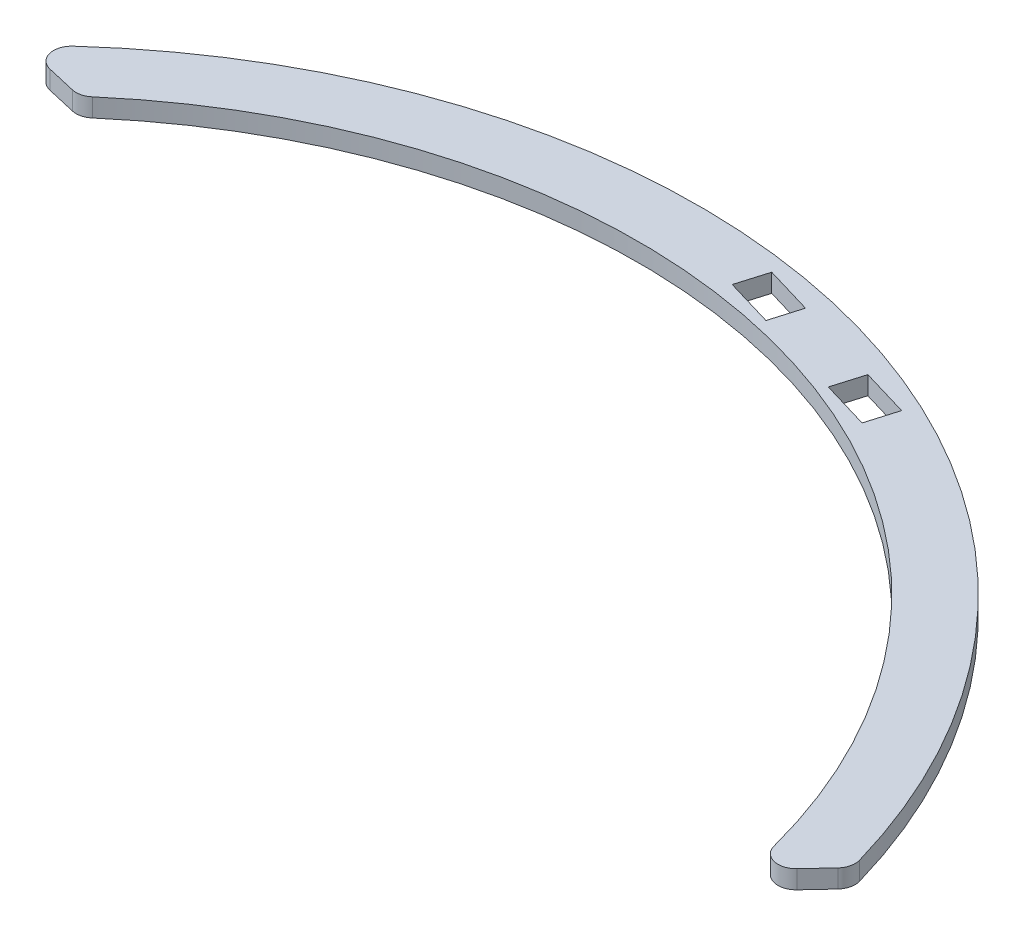
SolidWorks part; units mm, degrees
ref_plane "Спереди" through (0, 0, 0) normal (0, 0, 1) x (1, 0, 0)
ref_plane "Сверху" through (0, 0, 0) normal (0, 1, 0) x (1, 0, 0)
ref_plane "Справа" through (0, 0, 0) normal (1, 0, 0) x (0, 0, -1)
other "Configuration Table"
sketch "Эскиз2" plane through (0, 0, 0) normal (0, 1, 0) x (1, 0, 0)
  line L0 (97.9755, 20.0202) -> (106.1654, 28.7909)
  line L1 (-66.3257, 74.8391) -> (-78.0163, 77.5464)
  arc A0 (97.9755, 20.0202) -> (-66.3257, 74.8391) centre (0, 0) ccw
  arc A1 (106.1654, 28.7909) -> (-78.0163, 77.5464) centre (0, 0) ccw
  dimension "D1" = 110
  dimension "D3" = 100
  dimension "D2" = 12
  dimension "D4" = 120
extrude "Бобышка-Вытянуть1" add sketch "Эскиз2" along normal blind 3
sketch "Эскиз3" plane through (0, 3, 0) normal (0, 1, 0) x (1, 0, 0)
  line L0 (-78.0163, 77.5464) -> (-66.3257, 74.8391) construction
  line L5 (36.109, 94.9201) -> (43.9692, 92.584)
  line L6 (36.109, 94.9201) -> (37.5905, 99.9046)
  line L7 (37.5905, 99.9046) -> (45.4506, 97.5685)
  line L8 (43.9692, 92.584) -> (45.4506, 97.5685)
  line L9 (97.9755, 20.0202) -> (106.1654, 28.7909) construction
  line L10 (-72.171, 76.1928) -> (102.0704, 24.4056)
  line L11 (13.7363, 101.5696) -> (21.5964, 99.2335)
  line L12 (13.7363, 101.5696) -> (15.2177, 106.5541)
  line L13 (15.2177, 106.5541) -> (23.0779, 104.218)
  line L14 (21.5964, 99.2335) -> (23.0779, 104.218)
  line L15 (23.0779, 104.218) -> (37.5905, 99.9046)
  line L16 (14.9497, 50.2992) -> (30.3342, 102.0613)
  point P8 (17.6663, 100.4016)
  point P9 (40.0391, 93.752)
  point P10 (-72.171, 76.1928)
  point P11 (102.0704, 24.4056)
  dimension "D1" = 5.2
  dimension "D2" = 8.2
  dimension "D3" = 54
  dimension "D4" = 23.34
extrude "Вырез-Вытянуть3" cut sketch "Эскиз3" against normal blind 5 contours L13 L12 L11 L14 | L7 L8 L5 L6
fillet "Скругление5" radius 3 4 edges at (106.1654, 1.5, -28.7909) (97.9755, 1.5, -20.0202) (-78.0163, 1.5, -77.5464) (-66.3257, 1.5, -74.8391)
